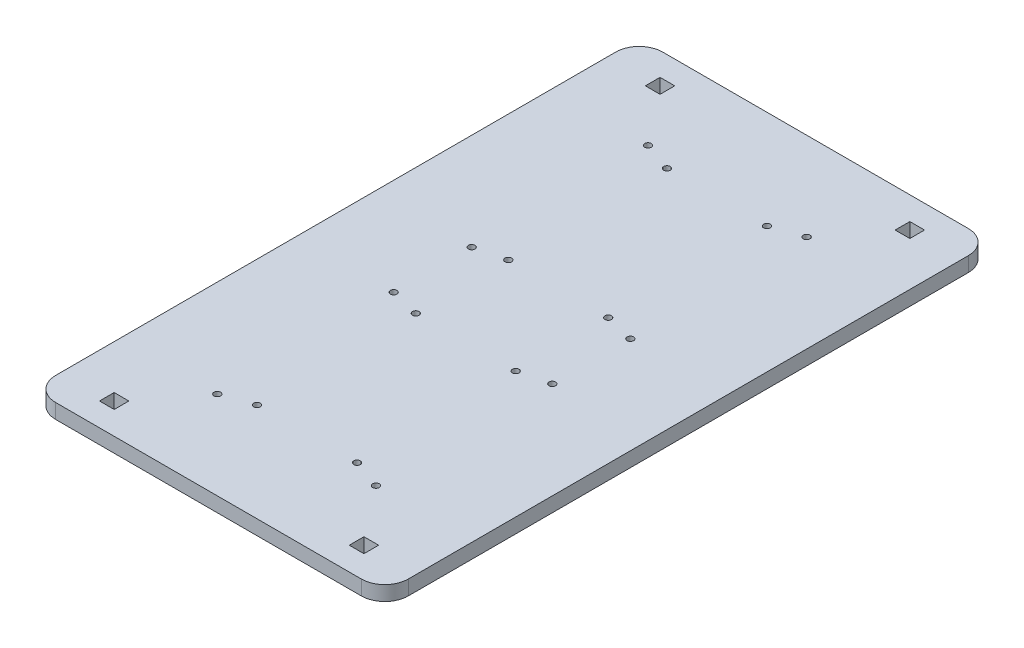
SolidWorks part; units mm, degrees
ref_plane "Front Plane" through (0, 0, 0) normal (0, 0, 1) x (1, 0, 0)
ref_plane "Top Plane" through (0, 0, 0) normal (0, 1, 0) x (1, 0, 0)
ref_plane "Right Plane" through (0, 0, 0) normal (1, 0, 0) x (0, 0, -1)
sketch "Sketch3" plane through (0, 0, 0) normal (0, 1, 0) x (1, 0, 0)
  line L4 (152.4, 0) -> (0, 0)
  line L5 (76.2, 262.3393) -> (76.2, 0) construction
  line L6 (19.05, 16.3877) -> (25.4, 16.3877)
  line L7 (19.05, 16.3877) -> (19.05, 10.0377)
  line L8 (19.05, 10.0377) -> (25.4, 10.0377)
  line L9 (25.4, 16.3877) -> (25.4, 10.0377)
  line L10 (133.35, 10.0377) -> (127, 10.0377)
  line L11 (127, 16.3877) -> (127, 10.0377)
  line L12 (133.35, 16.3877) -> (127, 16.3877)
  line L13 (133.35, 16.3877) -> (133.35, 10.0377)
  line L14 (0, 0) -> (0, 262.3393)
  line L15 (0, 262.3393) -> (152.4, 262.3393)
  line L16 (152.4, 262.3393) -> (152.4, 0)
  line L17 (0, 131.1696) -> (152.4, 131.1696) construction
  line L18 (133.35, 245.9515) -> (133.35, 252.3015)
  line L19 (133.35, 245.9515) -> (127, 245.9515)
  line L20 (127, 245.9515) -> (127, 252.3015)
  line L21 (133.35, 252.3015) -> (127, 252.3015)
  line L22 (19.05, 252.3015) -> (25.4, 252.3015)
  line L23 (25.4, 245.9515) -> (25.4, 252.3015)
  line L24 (19.05, 245.9515) -> (25.4, 245.9515)
  line L25 (19.05, 245.9515) -> (19.05, 252.3015)
  circle A6 centre (41.91, 38.1) radius 1.4224
  circle A7 centre (41.91, 114.3) radius 1.4224
  circle A8 centre (110.49, 114.3) radius 1.4224
  circle A9 centre (110.49, 38.1) radius 1.4224
  circle A10 centre (54.61, 151.1577) radius 1.4224
  circle A11 centre (54.61, 219.7377) radius 1.4224
  circle A12 centre (97.79, 151.1577) radius 1.4224
  circle A13 centre (97.79, 219.7377) radius 1.4224
  circle A14 centre (97.79, 42.6016) radius 1.4224
  circle A15 centre (97.79, 111.1816) radius 1.4224
  circle A16 centre (54.61, 111.1816) radius 1.4224
  circle A17 centre (54.61, 42.6016) radius 1.4224
  circle A18 centre (110.49, 148.0393) radius 1.4224
  circle A19 centre (110.49, 224.2393) radius 1.4224
  circle A20 centre (41.91, 224.2393) radius 1.4224
  circle A21 centre (41.91, 148.0393) radius 1.4224
  dimension "D2" = 19.05
  dimension "D10" = 38.1
  dimension "D13" = 68.58
  dimension "D5" = 152.4
  dimension "D6" = 6.35
  dimension "D7" = 6.35
  dimension "D11" = 76.2
  dimension "D12" = 68.58
  dimension "D14" = 43.18
extrude "Boss-Extrude1" add sketch "Sketch3" along normal blind 6.35
fillet "Fillet1" radius 10.16 4 edges at (0, 3.175, 0) (0, 3.175, -262.3393) (152.4, 3.175, 0) (152.4, 3.175, -262.3393)
